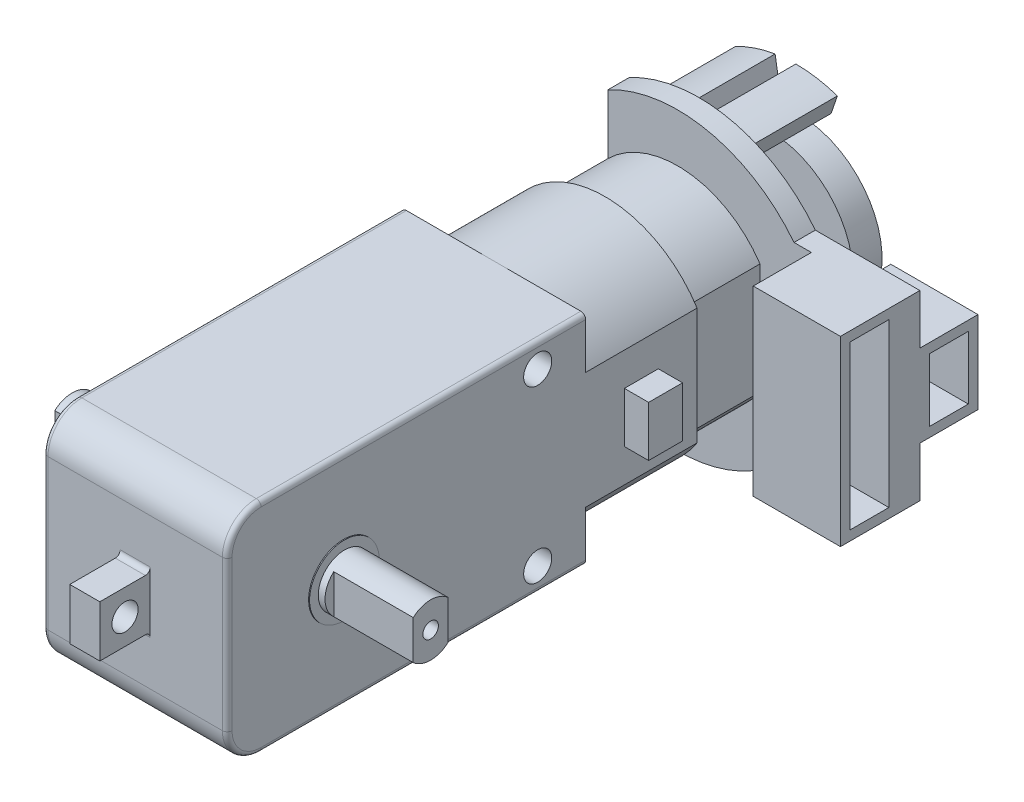
SolidWorks part; units mm, degrees
ref_plane "Front Plane" through (0, 0, 0) normal (0, 0, 1) x (1, 0, 0)
ref_plane "Top Plane" through (0, 0, 0) normal (0, 1, 0) x (1, 0, 0)
ref_plane "Right Plane" through (0, 0, 0) normal (1, 0, 0) x (0, 0, -1)
sketch "Sketch1" plane through (0, 0, 0) normal (1, 0, 0) x (0, 0, -1)
  line L0 (0, 0) -> (-38.2014, 0) construction
  line L2 (-37, -11.25) -> (0, -11.25)
  line L3 (-37, -11.25) -> (-37, 11.25)
  line L4 (-37, 11.25) -> (0, 11.25)
  line L5 (0, -11.25) -> (0, 11.25)
  line L6 (-37, -11.25) -> (0, 11.25) construction
  line L7 (-37, 11.25) -> (0, -11.25) construction
  point P3 (-18.5, 0)
  dimension "D1" = 22.5
  dimension "D2" = 37
extrude "Boss-Extrude1" add sketch "Sketch1" along normal blind 19
sketch "Sketch2" plane through (0, 0, 37) normal (0, 0, 1) x (1, 0, 0)
  line L0 (9.5, 11.25) -> (9.5, -11.25) construction
  line L1 (19, 11.25) -> (0, 11.25) construction
  line L2 (19, -11.25) -> (0, -11.25) construction
  line L3 (0, 0) -> (19, 0) construction
  line L4 (19, 11.25) -> (19, -11.25) construction
  line L6 (7.95, -2.65) -> (11.05, -2.65)
  line L7 (7.95, -2.65) -> (7.95, 2.65)
  line L8 (7.95, 2.65) -> (11.05, 2.65)
  line L9 (11.05, -2.65) -> (11.05, 2.65)
  line L10 (7.95, -2.65) -> (11.05, 2.65) construction
  line L11 (7.95, 2.65) -> (11.05, -2.65) construction
  point P11 (9.5, 0)
  dimension "D1" = 3.1
  dimension "D2" = 5.3
extrude "Boss-Extrude2" add sketch "Sketch2" along normal blind 5.2
sketch "Sketch3" plane through (11.05, 0, 0) normal (1, 0, 0) x (0, 0, -1)
  line L0 (-42.2, 2.65) -> (-37, -2.65) construction
  line L1 (-42.2, -2.65) -> (-37, 2.65) construction
  line L2 (-37, 11.25) -> (-37, -11.25) construction
  line L3 (-37, -2.65) -> (-37, 2.65) construction
  line L4 (-42.2, 2.65) -> (-37, 2.65) construction
  circle A0 centre (-39.6, 0) radius 1.35
  dimension "D1" = 2.7
extrude "Cut-Extrude1" cut sketch "Sketch3" against normal through all
fillet "Fillet1" radius 3.5 2 edges at (9.5, -11.25, 37) (9.5, 11.25, 37)
sketch "Sketch4" plane through (19, 0, 0) normal (1, 0, 0) x (0, 0, -1)
  line L0 (-25, 11.25) -> (-25, -11.25) construction
  line L1 (0, 11.25) -> (-33.5, 11.25) construction
  line L2 (-33.5, -11.25) -> (0, -11.25) construction
  line L3 (-37, 0) -> (0, 0) construction
  line L4 (-37, 7.75) -> (-37, -7.75) construction
  circle A0 centre (-25, 0) radius 3.6
  dimension "D2" = 7.2
  dimension "D1" = 12
extrude "Boss-Extrude3" add sketch "Sketch4" along normal blind 0.1
sketch "Sketch5" plane through (0, 0, 0) normal (-1, 0, 0) x (0, 0, 1)
  circle A0 centre (25, 0) radius 3.6 construction
  circle A1 centre (25, 0) radius 3.6
extrude "Boss-Extrude4" add sketch "Sketch5" along normal blind 0.1
sketch "Sketch6" plane through (19.1, 0, 0) normal (1, 0, 0) x (0, 0, -1)
  circle A0 centre (-25, 0) radius 2.7
  dimension "D1" = 5.4
extrude "Boss-Extrude5" add sketch "Sketch6" along normal blind 8.9
sketch "Sketch7" plane through (-0.1, 0, 0) normal (-1, 0, 0) x (0, 0, 1)
  circle A0 centre (25, 0) radius 2.7 construction
  circle A1 centre (25, 0) radius 2.7
extrude "Boss-Extrude6" add sketch "Sketch7" along normal blind 8.9
fillet "Fillet2" radius 0.5 2 edges at (9.5, -2.65, 37) (9.5, 2.65, 37)
sketch "Sketch8" plane through (28, 0, 0) normal (1, 0, 0) x (0, 0, -1)
  line L0 (-26.8, 2.0125) -> (-26.8, -2.0125)
  line L2 (-23.2, -2.0125) -> (-23.2, 2.0125)
  circle A0 centre (-25, 0) radius 2.7 construction
  circle A1 centre (-25, 0) radius 2.7
  circle M3 centre (-25, 0) radius 2.7
  dimension "D1" = 3.6
extrude "Cut-Extrude2" cut sketch "Sketch8" against normal blind 8.2 contours L0 M3 | L2 M3
sketch "Sketch9" plane through (-9, 0, 0) normal (-1, 0, 0) x (0, 0, 1)
  line L0 (26.8, 2.0125) -> (26.8, -2.0125) construction
  line L1 (23.2, -2.0125) -> (23.2, 2.0125) construction
  line L2 (26.8, 2.0125) -> (26.8, -2.0125)
  line L3 (23.2, -2.0125) -> (23.2, 2.0125)
  circle A0 centre (25, 0) radius 2.7 construction
  circle A1 centre (25, 0) radius 2.7
  circle M1 centre (25, 0) radius 2.7
extrude "Cut-Extrude3" cut sketch "Sketch9" against normal blind 8.2 contours L3 M1 | L2 M1
hole_wizard "M2x0.4 Tapped Hole1" positions "Sketch11" profile "Sketch10" tap size "M2x0.4" standard "ANSI Metric"
sketch "Sketch11" plane through (28, 0, 0) normal (1, 0, 0) x (0, 0, -1)
  point P0 (-25, 0)
sketch "Sketch10" plane through (28, 0, 25) normal (0, 1, 0) x (0, 0, -1)
  line L0 (0, 0) -> (0, 5.6807)
  line L1 (0, 5.6807) -> (0.8, 5.2)
  line L2 (0.8, 5.2) -> (0.8, 0)
  line L5 (0.8, 0) -> (0, 0)
  line L10 (0, 5.6807) -> (-0.8, 5.2) construction
  line L11 (0, -6.35) -> (0, 107.95) construction
  dimension "Tap Drill Dia." = 1.6
  dimension "Tap Drill Depth" = 5.2
  dimension "Drill Angle" = 118
cosmetic thread "Hole Thread1" parameters "D1"=4, "D2"=2
hole_wizard "M2x0.4 Tapped Hole2" positions "Sketch15" profile "Sketch14" tap size "M2x0.4" standard "ANSI Metric"
sketch "Sketch15" plane through (-9, 0, 0) normal (-1, 0, 0) x (0, 0, 1)
  point P0 (25, 0)
sketch "Sketch14" plane through (-9, 0, 25) normal (0, 1, 0) x (0, 0, 1)
  line L0 (0, 0) -> (0, 5.6807)
  line L1 (0, 5.6807) -> (0.8, 5.2)
  line L2 (0.8, 5.2) -> (0.8, 0)
  line L5 (0.8, 0) -> (0, 0)
  line L10 (0, 5.6807) -> (-0.8, 5.2) construction
  line L11 (0, -6.35) -> (0, 107.95) construction
  dimension "Tap Drill Dia." = 1.6
  dimension "Tap Drill Depth" = 5.2
  dimension "Drill Angle" = 118
cosmetic thread "Hole Thread2" parameters "D1"=4, "D2"=2
sketch "Sketch16" plane through (0, 0, 0) normal (-1, 0, 0) x (0, 0, 1)
  line L0 (0, 0) -> (21.4, 0) construction
  circle A0 centre (25, 0) radius 3.6 construction
  circle A1 centre (13.75, 0) radius 1.95
  circle A4 centre (25, 0) radius 3.6 construction
  dimension "D1" = 3.9
  dimension "D2" = 5.7
extrude "Boss-Extrude7" add sketch "Sketch16" along normal blind 2
sketch "Sketch17" plane through (0, 0, 0) normal (0, 0, -1) x (-1, 0, 0)
  line L0 (-19, 11.25) -> (0, -11.25) construction
  line L1 (-19, -11.25) -> (0, 11.25) construction
  line L2 (-19, -11.25) -> (-19, 11.25) construction
  line L3 (-19, -11.25) -> (-19, 11.25)
  line L6 (-1.3, -11.25) -> (-1.3, 11.25)
  line L7 (-1.3, -11.25) -> (-1.3, 11.25)
  circle A0 centre (-9.5, 0) radius 11.25
  dimension "D1" = 1.3
extrude "Boss-Extrude8" add sketch "Sketch17" along normal blind 11.5 contours L7 A0 L3
sketch "Sketch18" plane through (19, 0, 0) normal (1, 0, 0) x (0, 0, -1)
  line L0 (11.5, 0) -> (0, 0) construction
  line L1 (11.5, 6.026) -> (11.5, -6.026) construction
  line L3 (4, -2.6) -> (7.5, -2.6)
  line L4 (4, -2.6) -> (4, 2.6)
  line L5 (4, 2.6) -> (7.5, 2.6)
  line L6 (7.5, -2.6) -> (7.5, 2.6)
  line L7 (4, -2.6) -> (7.5, 2.6) construction
  line L8 (4, 2.6) -> (7.5, -2.6) construction
  point P5 (5.75, 0)
  dimension "D1" = 4
  dimension "D2" = 5.2
  dimension "D3" = 3.5
extrude "Boss-Extrude9" add sketch "Sketch18" along normal blind 2.5
sketch "Sketch19" plane through (1.3, 0, 0) normal (-1, 0, 0) x (0, 0, 1)
  line L0 (-7.5, 2.6) -> (-4, 2.6) construction
  line L1 (-4, 2.6) -> (-4, -2.6) construction
  line L2 (-4, -2.6) -> (-7.5, -2.6) construction
  line L3 (-7.5, -2.6) -> (-7.5, 2.6) construction
  line L4 (-7.5, 2.6) -> (-4, 2.6)
  line L5 (-4, 2.6) -> (-4, -2.6)
  line L6 (-4, -2.6) -> (-7.5, -2.6)
  line L7 (-7.5, -2.6) -> (-7.5, 2.6)
extrude "Boss-Extrude10" add sketch "Sketch19" along normal blind 2.5
sketch "Sketch20" plane through (0, 0, -11.5) normal (0, 0, -1) x (-1, 0, 0)
  line L20 (-18, 6.026) -> (-18, -6.026)
  line L21 (-18, 5.7282) -> (-18, -5.7282)
  line L23 (-2.3, -7.7021) -> (-2.3, 7.7021)
  line L24 (-2.3, -7.2954) -> (-2.3, 7.2954)
  arc A30 (-2.0289, 7.0175) -> (-18.1556, 5.4903) centre (-9.5, 0) ccw
  arc A31 (-2.3, 7.2954) -> (-18, 5.7282) centre (-9.5, 0) ccw
  arc A34 (-18.1556, -5.4903) -> (-2.0289, -7.0175) centre (-9.5, 0) ccw
  arc A35 (-18, -5.7282) -> (-2.3, -7.2954) centre (-9.5, 0) ccw
  dimension "D1" = 1
  dimension "D2" = 1
  dimension "D3" = 1
  dimension "D4" = 1
extrude "Boss-Extrude11" add sketch "Sketch20" along normal blind 13.5
fillet "Fillet3" radius 1.7 2 edges at (10.5181, -10.1993, -25) (10.5181, 10.1993, -25)
sketch "Sketch21" plane through (0, 0, -25) normal (0, 0, -1) x (-1, 0, 0)
  line L0 (-5.5, 3) -> (-5.5, -3)
  circle A0 centre (-9.5, 0) radius 5
  dimension "D1" = 10
  dimension "D2" = 9
extrude "Boss-Extrude12" add sketch "Sketch21" along normal blind 2 contours L0 A0
sketch "Sketch23" plane through (0, 0, -25) normal (0, 0, -1) x (-1, 0, 0)
  line L0 (-9.5, 10.25) -> (-9.5, -11.25) construction
  line L1 (-7.9, 7) -> (-7.9, -7) construction
  line L2 (-11.1, 13.5) -> (-7.9, 13.5)
  line L3 (-11.1, 13.5) -> (-11.1, 7)
  line L4 (-11.1, 7) -> (-7.9, 7)
  line L5 (-7.9, 13.5) -> (-7.9, 7)
  line L6 (-11.1, 13.5) -> (-7.9, 7) construction
  line L7 (-11.1, 7) -> (-7.9, 13.5) construction
  line L8 (-11.1, -15.5) -> (-7.9, -15.5)
  line L9 (-11.1, -15.5) -> (-11.1, -7)
  line L10 (-11.1, -7) -> (-7.9, -7)
  line L11 (-7.9, -15.5) -> (-7.9, -7)
  line L12 (-11.1, -15.5) -> (-7.9, -7) construction
  line L13 (-11.1, -7) -> (-7.9, -15.5) construction
  line L14 (-9.5, 0) -> (-7.9, 7) construction
  line L16 (-9.5, 0) -> (-7.9, -7) construction
  arc A0 (-2.3, 7.2954) -> (-18, 5.7282) centre (-9.5, 0) ccw construction
  arc A1 (-2.3, 4.6111) -> (-18, 0.9233) centre (-9.5, 0) ccw construction
  arc A2 (-2.3, 4.6111) -> (-18, 0.9233) centre (-9.5, 0) ccw construction
  dimension "D1" = 14
  dimension "D2" = 3.2
extrude "Cut-Extrude4" cut sketch "Sketch23" against normal blind 6
sketch "Sketch24" plane through (0, -11.25, 0) normal (0, -1, 0) x (1, 0, 0)
  line L0 (19, 25) -> (0, 25) construction
  line L1 (19, 33.5) -> (19, 0) construction
  line L2 (0, 33.5) -> (0, 0) construction
  line L3 (28, 25) -> (19, 25) construction
  line L4 (28, 23.2) -> (28, 26.8) construction
ref_plane "Plane1" through (0, 0, 25) normal (0, 0, 1) x (-1, 0, 0)
sketch "Sketch25" plane through (19, 0, 0) normal (1, 0, 0) x (0, 0, -1)
  line L0 (-4.95, 11.25) -> (-4.95, -11.25) construction
  line L1 (0, 11.25) -> (-33.5, 11.25) construction
  line L2 (-33.5, -11.25) -> (0, -11.25) construction
  line L4 (0, 6.026) -> (0, 11.25) construction
  line L5 (-37, 7.75) -> (-37, -7.75) construction
  circle A0 centre (-4.95, 8.8) radius 1.45
  circle A1 centre (-4.95, -8.8) radius 1.45
  dimension "D1" = 2.9
  dimension "D2" = 14.7
  dimension "D5" = 3.5
  dimension "D3" = 1
  dimension "D4" = 1
  dimension "D6" = 30.6
extrude "Cut-Extrude5" cut sketch "Sketch25" against normal through all
fillet "Fillet4" radius 0.5 10 edges at (0, -11.25, 16.75) (0, -10.2249, 35.9749) (0, 0, 37) (0, 10.2249, 35.9749) (19, -11.25, 16.75) (19, -10.2249, 35.9749) (19, 0, 37) (19, 10.2249, 35.9749) (0, 11.25, 16.75) (19, 11.25, 16.75)
sketch "Sketch26" plane through (0, 0, -27) normal (0, 0, -1) x (-1, 0, 0)
  circle A0 centre (-9.5, 0) radius 1
  dimension "D1" = 2
extrude "Boss-Extrude13" add sketch "Sketch26" along normal blind 4.5
sketch "Sketch27" plane through (0, 0, 0) normal (-1, 0, 0) x (0, 0, 1)
  line L0 (25, 0) -> (16.1055, -5.3723) construction
sketch "Sketch28" plane through (0, 0, -31.5) normal (0, 0, -1) x (-1, 0, 0)
  circle A0 centre (-9.5, 0) radius 8.6
  dimension "D1" = 17.2
extrude "Boss-Extrude14" add sketch "Sketch28" against normal blind 3
sketch "Sketch29" plane through (0, 0, -19) normal (0, 0, -1) x (-1, 0, 0)
  line L0 (-18, 5.7282) -> (-18, -5.7282) construction
  line L1 (-18, 5.7282) -> (-18, -5.7282)
  line L2 (-2.3, 7.2954) -> (-2.3, 13.4433)
  line L3 (-9.5, 0) -> (-39.9184, 0) construction
  line L4 (-23, 7.0931) -> (-23, -7.0931)
  line L5 (-2.3, 7.2954) -> (10.3813, 16.3683) construction
  line L6 (-2.3, -7.2954) -> (-2.3, -13.4433)
  line L7 (-7.9, -8.399) -> (-7.9, -10.1244) construction
  line L8 (-2.3, 13.4433) -> (7.472, 20.4347) construction
  line L9 (-32.3, -9.4) -> (-21.5084, -9.4)
  line L10 (-32.3, -9.4) -> (-32.3, 9.4)
  line L11 (-32.3, 9.4) -> (-21.5084, 9.4)
  line L12 (-21.5084, -9.4) -> (-21.5084, 9.4)
  line L13 (-32.3, -9.4) -> (-21.5084, 9.4) construction
  line L14 (-32.3, 9.4) -> (-21.5084, -9.4) construction
  line L15 (-11.1, -10.1244) -> (-11.1, -8.399) construction
  line L16 (-7.9, -8.399) -> (-7.9, -10.1244)
  line L17 (-11.1, -10.1244) -> (-11.1, -8.399)
  line L18 (-7.9, 10.1244) -> (-7.9, 8.399) construction
  line L19 (-11.1, 8.399) -> (-11.1, 10.1244) construction
  line L20 (-7.9, 10.1244) -> (-7.9, 8.399)
  line L21 (-11.1, 8.399) -> (-11.1, 10.1244)
  arc A0 (-2.3, 7.2954) -> (-18, 5.7282) centre (-9.5, 0) ccw construction
  arc A1 (-2.3, 7.2954) -> (-7.9, 10.1244) centre (-9.5, 0) ccw
  arc A2 (-18, -5.7282) -> (-2.3, -7.2954) centre (-9.5, 0) ccw construction
  arc A3 (-18, -5.7282) -> (-11.1, -10.1244) centre (-9.5, 0) ccw
  arc A4 (-2.3, 13.4433) -> (-23, 7.0931) centre (-9.5, 0) ccw
  arc A5 (-23, -7.0931) -> (-2.3, -13.4433) centre (-9.5, 0) ccw
  arc A6 (-23, -7.0931) -> (1.2122, -10.8541) centre (-9.5, 0) ccw construction
  arc A9 (-7.9, -10.1244) -> (-2.3, -7.2954) centre (-9.5, 0) ccw
  arc A10 (-18, -5.7282) -> (-2.3, -7.2954) centre (-9.5, 0) ccw construction
  arc A11 (-11.1, 10.1244) -> (-18, 5.7282) centre (-9.5, 0) ccw
  arc A12 (-2.3, 7.2954) -> (-18, 5.7282) centre (-9.5, 0) ccw construction
  arc A13 (-11.1, -10.1244) -> (-7.9, -10.1244) centre (-9.5, 0) ccw construction
  arc A14 (-11.1, -10.1244) -> (-7.9, -10.1244) centre (-9.5, 0) ccw
  arc A15 (-7.9, 10.1244) -> (-11.1, 10.1244) centre (-9.5, 0) ccw construction
  arc A16 (-7.9, 10.1244) -> (-11.1, 10.1244) centre (-9.5, 0) ccw
  arc A17 (-11.1, 9.2617) -> (-7.9, 9.2617) centre (-9.5, 11.7994) ccw
  arc A18 (-11.1, -9.2617) -> (-7.9, -9.2617) centre (-9.5, -11.7994) cw
  point P21 (-26.9042, 0)
  arc M18 (-7.9, 10.1244) -> (-11.1, 10.1244) centre (-9.5, 0) ccw
  line M19 (-11.1, 10.1244) -> (-11.1, 7)
  dimension "D1" = 3
  dimension "D5" = 3
  dimension "D3" = 18.8
  dimension "D4" = 30
  dimension "D2" = 5
extrude "Boss-Extrude20" add sketch "Sketch29" along normal blind 2.2 contours A14 A3 L1 A11 A1 L2 A4 L12 A5 L6 A9 M18 | A18 L17 A14 L16 | A17 L20 M19 M18 | A5 L4 A4 L11 L10 L9 | L4 A5 L12 A4
sketch "Sketch30" plane through (0, 0, -19) normal (0, 0, 1) x (1, 0, 0)
  line L0 (32.3, -9.4) -> (21.5084, -9.4) construction
  line L1 (32.3, 9.4) -> (23.3, 9.4)
  line L2 (32.3, 9.4) -> (32.3, -9.4)
  line L3 (32.3, -9.4) -> (23.3, -9.4)
  line L4 (23.3, 9.4) -> (23.3, -9.4)
  dimension "D1" = 9
extrude "Boss-Extrude21" add sketch "Sketch30" along normal blind 6
sketch "Sketch31" plane through (0, 0, -21.2) normal (0, 0, -1) x (-1, 0, 0)
  line L0 (-32.3, -9.4) -> (-32.3, 9.4) construction
  line L1 (-32.3, 4.25) -> (-23.3, 4.25)
  line L2 (-32.3, 4.25) -> (-32.3, -4.25)
  line L3 (-32.3, -4.25) -> (-23.3, -4.25)
  line L4 (-23.3, 4.25) -> (-23.3, -4.25)
  line L5 (-23.3, 0) -> (-9.5, 0) construction
  dimension "D1" = 9
  dimension "D2" = 8.5
extrude "Boss-Extrude22" add sketch "Sketch31" along normal blind 6
sketch "Sketch32" plane through (32.3, 0, 0) normal (1, 0, 0) x (0, 0, -1)
  line L8 (18, 8.4) -> (18, -8.4)
  line L9 (22.2, 3.25) -> (22.2, -3.25)
  line L10 (19, 15.25) -> (19, 9.4) construction
  line L11 (21.2, 5.7282) -> (21.2, 10.1244) construction
  line L16 (20.2, 8.4) -> (14, 8.4)
  line L17 (14, 8.4) -> (14, -8.4)
  line L18 (14, -8.4) -> (20.2, -8.4)
  line L19 (20.2, -8.4) -> (20.2, -3.25)
  line L20 (20.2, -3.25) -> (26.2, -3.25)
  line L21 (26.2, -3.25) -> (26.2, 3.25)
  line L22 (26.2, 3.25) -> (20.2, 3.25)
  line L23 (20.2, 3.25) -> (20.2, 8.4)
  line L24 (20.2, 8.4) -> (14, 8.4)
  line L25 (14, 8.4) -> (14, -8.4)
  line L26 (14, -8.4) -> (20.2, -8.4)
  line L27 (20.2, -8.4) -> (20.2, -3.25)
  line L28 (20.2, -3.25) -> (26.2, -3.25)
  line L29 (26.2, -3.25) -> (26.2, 3.25)
  line L30 (26.2, 3.25) -> (20.2, 3.25)
  line L31 (20.2, 3.25) -> (20.2, 8.4)
  dimension "D2" = 1
  dimension "D3" = 1
  dimension "D1" = 1
extrude "Cut-Extrude6" cut sketch "Sketch32" against normal blind 6 contours L25 L26 L8 L24 | L29 L30 L9 L28
sketch "Sketch33" plane through (0, 0, -21.2) normal (0, 0, -1) x (-1, 0, 0)
  line L0 (-7.035, 15.0495) -> (-7.035, -15.0495) construction
  line L1 (-2.3, 13.4433) -> (-9.5, 0)
  line L2 (-9.5, 0) -> (-2.3, -13.4433)
  line L3 (-9.5, 0) -> (-7.035, 15.0495)
  line L4 (-9.5, 0) -> (-7.035, -15.0495)
  line L5 (-9.5, 0) -> (-9.5, 15.25)
  line L6 (-9.5, 0) -> (-9.5, -15.25)
  line L7 (-9.5, 0) -> (-14.4324, 14.4303)
  line L8 (-9.5, 0) -> (-14.4324, -14.4303)
  line L9 (-14.4324, 14.4303) -> (-14.4324, -14.4303) construction
  circle A0 centre (-9.5, 0) radius 11.25
  circle A1 centre (-9.5, 0) radius 13.25
  arc A2 (-2.3, 7.2954) -> (-7.9, 10.1244) centre (-9.5, 0) ccw construction
  arc A3 (-2.3, 13.4433) -> (-21.5084, 9.4) centre (-9.5, 0) ccw construction
  arc A4 (-21.5084, -9.4) -> (-2.3, -13.4433) centre (-9.5, 0) ccw construction
  dimension "D1" = 1
  dimension "D2" = 2
  dimension "D3" = 5
  dimension "D4" = 5
extrude "Boss-Extrude23" add sketch "Sketch33" along normal blind 10 contours L5 A1 L7 A0 | L1 A1 L3 A0 | L8 A1 L6 A0 | L4 A1 L2 A0
